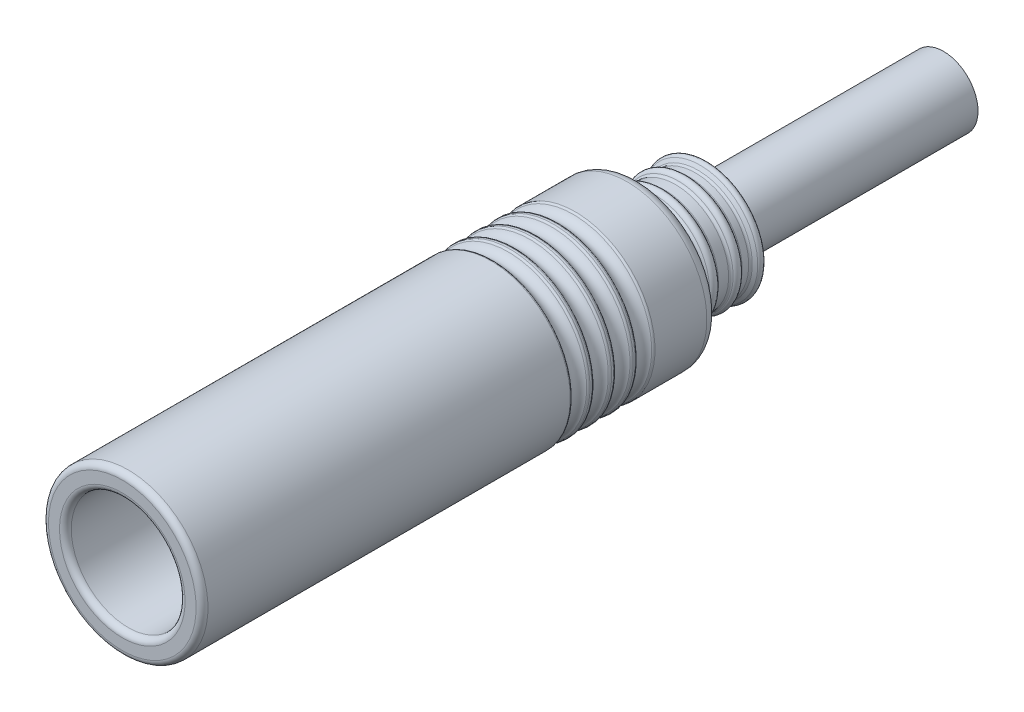
SolidWorks part; units mm, degrees
ref_plane "Front Plane" through (0, 0, 0) normal (0, 0, 1) x (1, 0, 0)
ref_plane "Top Plane" through (0, 0, 0) normal (0, 1, 0) x (1, 0, 0)
ref_plane "Right Plane" through (0, 0, 0) normal (1, 0, 0) x (0, 0, -1)
sketch "Sketch1" plane through (0, 0, 0) normal (1, 0, 0) x (0, 0, -1)
  line L0 (0, 5.315) -> (0, 6.25)
  line L1 (0.5, 6.75) -> (42.7261, 6.75)
  line L2 (43.7171, 5.884) -> (43.8171, 5.1442)
  line L3 (44.1195, 4.75) -> (44.6706, 4.5194)
  line L4 (44.7671, 4.5) -> (44.8171, 4.5)
  line L5 (48.7183, 4.6021) -> (48.913, 4.8673)
  line L6 (49.5, 4.675) -> (49.5, 0)
  line L7 (49.5, 0) -> (8.37, 0)
  line L8 (8.37, 0) -> (8.37, 4.815)
  line L9 (8.37, 4.815) -> (0.5, 4.815)
  line L10 (45.9627, 4.5) -> (46.8171, 4.5)
  line L11 (47.9627, 4.5) -> (48.5168, 4.5)
  arc A0 (0, 5.315) -> (0.5, 4.815) centre (0.5, 5.315) ccw
  arc A1 (0, 6.25) -> (0.5, 6.75) centre (0.5, 6.25) cw
  arc A2 (42.7261, 6.75) -> (43.7171, 5.884) centre (42.7261, 5.75) cw
  arc A3 (45.7336, 4.65) -> (45.0462, 4.65) centre (45.3899, 4.5) ccw
  arc A4 (47.7336, 4.65) -> (47.0462, 4.65) centre (47.3899, 4.5) ccw
  arc A6 (48.913, 4.8673) -> (49.5, 4.675) centre (49.175, 4.675) cw
  arc A7 (47.7336, 4.65) -> (47.9627, 4.5) centre (47.9627, 4.75) ccw
  arc A8 (45.7336, 4.65) -> (45.9627, 4.5) centre (45.9627, 4.75) ccw
  arc A9 (45.0462, 4.65) -> (44.8171, 4.5) centre (44.8171, 4.75) cw
  arc A10 (44.6706, 4.5194) -> (44.7671, 4.5) centre (44.7671, 4.75) ccw
  arc A11 (48.5168, 4.5) -> (48.7183, 4.6021) centre (48.5168, 4.75) ccw
  arc A12 (47.0462, 4.65) -> (46.8171, 4.5) centre (46.8171, 4.75) cw
  arc A13 (43.8171, 5.1442) -> (44.1195, 4.75) centre (44.3126, 5.2112) ccw
  arc A14 (36.8406, 6.6453) -> (38.1594, 6.6453) centre (37.5, 7.0025) ccw
  arc A15 (38.3353, 6.75) -> (38.1594, 6.6453) centre (38.3353, 6.55) ccw
  arc A16 (36.8406, 6.6453) -> (36.6647, 6.75) centre (36.6647, 6.55) ccw
  arc A17 (35.0072, 6.6453) -> (34.8314, 6.75) centre (34.8314, 6.55) ccw
  arc A18 (35.0072, 6.6453) -> (36.3261, 6.6453) centre (35.6667, 7.0025) ccw
  arc A19 (36.502, 6.75) -> (36.3261, 6.6453) centre (36.502, 6.55) ccw
  arc A20 (33.1739, 6.6453) -> (32.998, 6.75) centre (32.998, 6.55) ccw
  arc A21 (33.1739, 6.6453) -> (34.4928, 6.6453) centre (33.8333, 7.0025) ccw
  arc A22 (34.6686, 6.75) -> (34.4928, 6.6453) centre (34.6686, 6.55) ccw
  arc A23 (31.3406, 6.6453) -> (31.1647, 6.75) centre (31.1647, 6.55) ccw
  arc A24 (31.3406, 6.6453) -> (32.6594, 6.6453) centre (32, 7.0025) ccw
  arc A25 (32.8353, 6.75) -> (32.6594, 6.6453) centre (32.8353, 6.55) ccw
  point P16 (0, 6.75)
  point P19 (43.6, 6.75)
  point P26 (0, 0)
  point P29 (49.175, 5)
  point P30 (47.3899, 4.875)
  point P33 (37.5, 6.2525)
  point P40 (47.7649, 4.5)
  point P43 (45.7649, 4.5)
  point P54 (47.0149, 4.5)
  point P76 (37.6755, 6.6453)
  dimension "D6" = 0.5
  dimension "D7" = 1
  dimension "D9" = 0.25
  dimension "D12" = 0.25
  dimension "D11" = 0.375
  dimension "D13" = 0.5
  dimension "D15" = 1
  dimension "D18" = 0.325
  dimension "D21" = 0.75
  dimension "D22" = 0.2
  dimension "D1" = 8.37
  dimension "D2" = 4.815
  dimension "D3" = 6.75
  dimension "D4" = 49.5
  dimension "D5" = 43.6
  dimension "D8" = 4.5
  dimension "D10" = 5
  dimension "D14" = 0.1
  dimension "D16" = 2
  dimension "D17" = 0.05
  dimension "D20" = 5.5
  dimension "D23" = 6.2525
  dimension "D24" = 32
  dimension "D19" = 4
revolve "Revolve1" add sketch "Sketch1" angle 360 about L7
sketch "Sketch2" plane through (0, 0, -49.5) normal (0, 0, -1) x (-1, 0, 0)
  circle A0 centre (0, 0) radius 2.92
extrude "Boss-Extrude1" add sketch "Sketch2" along normal blind 20
